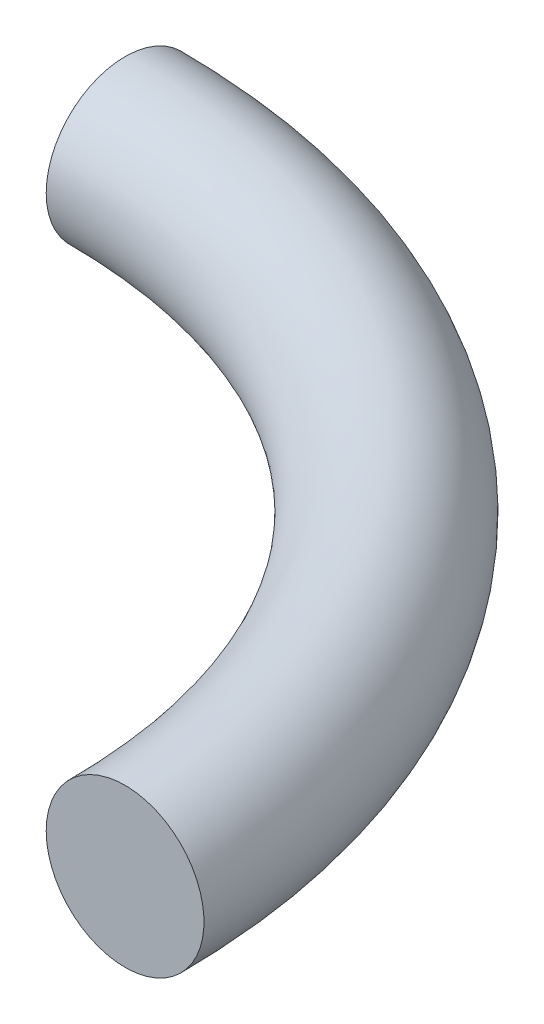
SolidWorks part; units mm, degrees
ref_plane "Front Plane" through (0, 0, 0) normal (0, 0, 1) x (1, 0, 0)
ref_plane "Top Plane" through (0, 0, 0) normal (0, 1, 0) x (1, 0, 0)
ref_plane "Right Plane" through (0, 0, 0) normal (1, 0, 0) x (0, 0, -1)
sketch "Sketch1" plane through (0, 0, 0) normal (0, 1, 0) x (1, 0, 0)
  arc A0 (50.8, 0) -> (0, 50.8) centre (0, 0) ccw
  point P6 (16.7271, 30.9528)
  dimension "D1" = 50.8
  dimension "D2" = 50.8
sweep "Sweep1" add path "Sketch1" circular profile diameter 12.7 parameters "D3"=12.7
